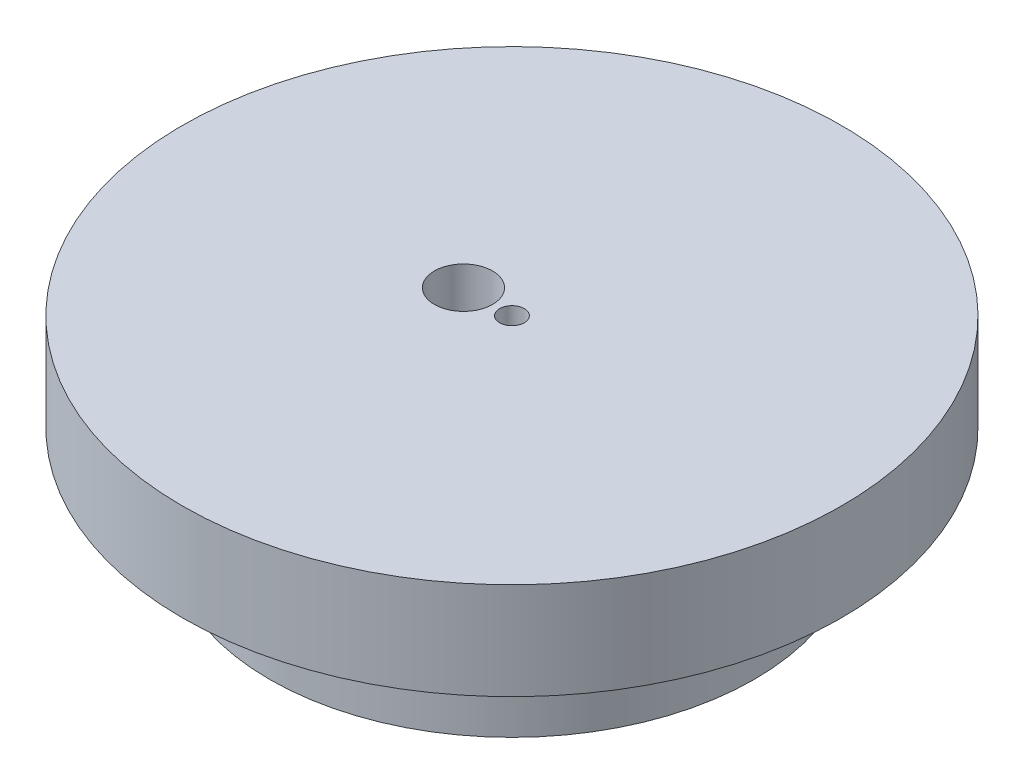
SolidWorks part; units mm, degrees
ref_plane "Front Plane" through (0, 0, 0) normal (0, 0, 1) x (1, 0, 0)
ref_plane "Top Plane" through (0, 0, 0) normal (0, 1, 0) x (1, 0, 0)
ref_plane "Right Plane" through (0, 0, 0) normal (1, 0, 0) x (0, 0, -1)
sketch "Sketch1" plane through (0, 0, 0) normal (0, 1, 0) x (1, 0, 0)
  line L2 (-1.5068, 11.05) -> (1.5068, 11.05)
  line L3 (-1.5068, 11.05) -> (-2.437, 8.1835)
  line L4 (1.5068, 11.05) -> (2.437, 8.1835)
  line L5 (6.748, 8.879) -> (4.0634, 7.5098)
  line L6 (6.748, 8.879) -> (8.879, 6.748)
  line L7 (8.879, 6.748) -> (7.5098, 4.0634)
  line L8 (11.05, 1.5068) -> (8.1835, 2.437)
  line L9 (11.05, 1.5068) -> (11.05, -1.5068)
  line L10 (11.05, -1.5068) -> (8.1835, -2.437)
  line L11 (8.879, -6.748) -> (7.5098, -4.0634)
  line L64 (8.879, -6.748) -> (6.748, -8.879)
  line L65 (6.748, -8.879) -> (4.0634, -7.5098)
  line L66 (1.5068, -11.05) -> (2.437, -8.1835)
  line L67 (1.5068, -11.05) -> (-1.5068, -11.05)
  line L68 (-1.5068, -11.05) -> (-2.437, -8.1835)
  line L69 (-6.748, -8.879) -> (-4.0634, -7.5098)
  line L70 (-6.748, -8.879) -> (-8.879, -6.748)
  line L71 (-8.879, -6.748) -> (-7.5098, -4.0634)
  line L72 (-11.05, -1.5068) -> (-8.1835, -2.437)
  line L73 (-11.05, -1.5068) -> (-11.05, 1.5068)
  line L74 (-11.05, 1.5068) -> (-8.1835, 2.437)
  line L75 (-8.879, 6.748) -> (-7.5098, 4.0634)
  line L76 (-8.879, 6.748) -> (-6.748, 8.879)
  line L77 (-6.748, 8.879) -> (-4.0634, 7.5098)
  circle A23 centre (0, 0) radius 25
  circle A26 centre (0, 0) radius 8.5386 construction
  arc A27 (2.437, 8.1835) -> (4.0634, 7.5098) centre (0, 0) cw
  arc A28 (7.5098, 4.0634) -> (8.1835, 2.437) centre (0, 0) cw
  arc A29 (8.1835, -2.437) -> (7.5098, -4.0634) centre (0, 0) cw
  arc A30 (4.0634, -7.5098) -> (2.437, -8.1835) centre (0, 0) cw
  arc A31 (-2.437, -8.1835) -> (-4.0634, -7.5098) centre (0, 0) cw
  arc A32 (-7.5098, -4.0634) -> (-8.1835, -2.437) centre (0, 0) cw
  arc A33 (-8.1835, 2.437) -> (-7.5098, 4.0634) centre (0, 0) cw
  arc A34 (-4.0634, 7.5098) -> (-2.437, 8.1835) centre (0, 0) cw
  point P8 (0, 0)
  point P9 (0, 0)
  point P47 (0, 0)
  dimension "D1" = 50
extrude "Boss-Extrude1" add sketch "Sketch1" along normal blind 10
sketch "Sketch2" plane through (0, 10, 0) normal (0, 1, 0) x (1, 0, 0)
  circle A0 centre (0, 0) radius 1.27
  circle A1 centre (0, 0) radius 34
  dimension "D1" = 2.54
  dimension "D2" = 68
extrude "Boss-Extrude2" add sketch "Sketch2" along normal blind 10
sketch "Sketch3" plane through (0, 20, 0) normal (0, 1, 0) x (1, 0, 0)
  circle A0 centre (-5, 0) radius 3
  dimension "D2" = 6
  dimension "D1" = 5
extrude "Cut-Extrude1" cut sketch "Sketch3" against normal through all
